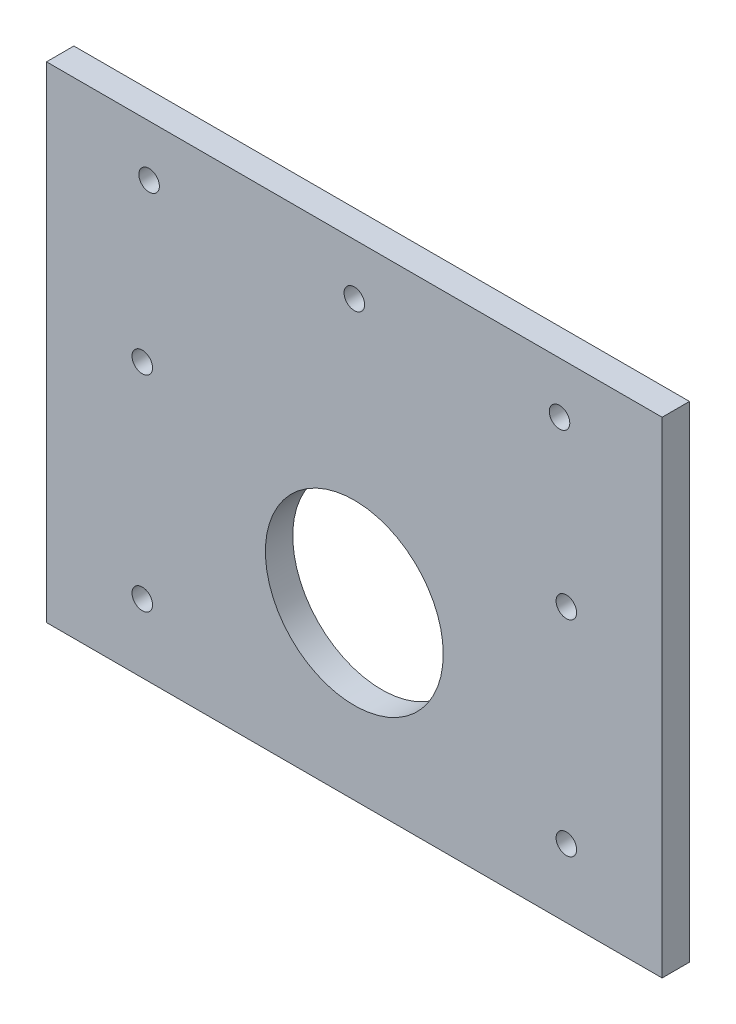
SolidWorks part; units mm, degrees
material "A-玻璃纤维"
ref_plane "前视基准面" through (0, 0, 0) normal (0, 0, 1) x (1, 0, 0)
ref_plane "上视基准面" through (0, 0, 0) normal (0, 1, 0) x (1, 0, 0)
ref_plane "右视基准面" through (0, 0, 0) normal (1, 0, 0) x (0, 0, -1)
sketch "草图1" plane through (0, 0, 0) normal (0, 0, 1) x (1, 0, 0)
  line L1 (-45, 35.5) -> (45, 35.5)
  line L2 (-45, 35.5) -> (-45, -35.5)
  line L3 (-45, -35.5) -> (45, -35.5)
  line L4 (45, 35.5) -> (45, -35.5)
  line L5 (-45, 35.5) -> (45, -35.5) construction
  line L6 (-45, -35.5) -> (45, 35.5) construction
  point P0 (0, 0)
  dimension "D1" = 90
  dimension "D2" = 71
extrude "凸台-拉伸1" add sketch "草图1" along normal blind 4
sketch "草图2" plane through (0, 0, 4) normal (0, 0, 1) x (1, 0, 0)
  line L0 (0, 35.5) -> (0, -35.5) construction
  line L1 (45, 35.5) -> (-45, 35.5) construction
  line L2 (-45, -35.5) -> (45, -35.5) construction
  circle A0 centre (0, 28) radius 1.5
  circle A1 centre (-30, 28) radius 1.5
  circle A3 centre (30, 28) radius 1.5
  dimension "D1" = 3
  dimension "D2" = 30
  dimension "D3" = 7.5
extrude "切除-拉伸1" cut sketch "草图2" against normal through all
sketch "草图3" plane through (0, 0, 4) normal (0, 0, 1) x (1, 0, 0)
  line L0 (0, 35.5) -> (0, -35.5) construction
  line L1 (45, 35.5) -> (-45, 35.5) construction
  line L2 (-45, -35.5) -> (45, -35.5) construction
  line L4 (-31, 4.5) -> (31, 4.5) construction
  line L5 (-31, 4.5) -> (-31, -25.5) construction
  line L6 (-31, -25.5) -> (31, -25.5) construction
  line L7 (31, 4.5) -> (31, -25.5) construction
  line L8 (-31, 4.5) -> (31, -25.5) construction
  line L9 (-31, -25.5) -> (31, 4.5) construction
  circle A0 centre (0, -10.5) radius 13
  circle A1 centre (-31, 4.5) radius 1.5
  circle A2 centre (-31, -25.5) radius 1.5
  circle A3 centre (31, -25.5) radius 1.5
  circle A4 centre (31, 4.5) radius 1.5
  dimension "D1" = 46
  dimension "D2" = 26
  dimension "D5" = 3
  dimension "D3" = 62
  dimension "D4" = 30
extrude "切除-拉伸2" cut sketch "草图3" against normal through all
